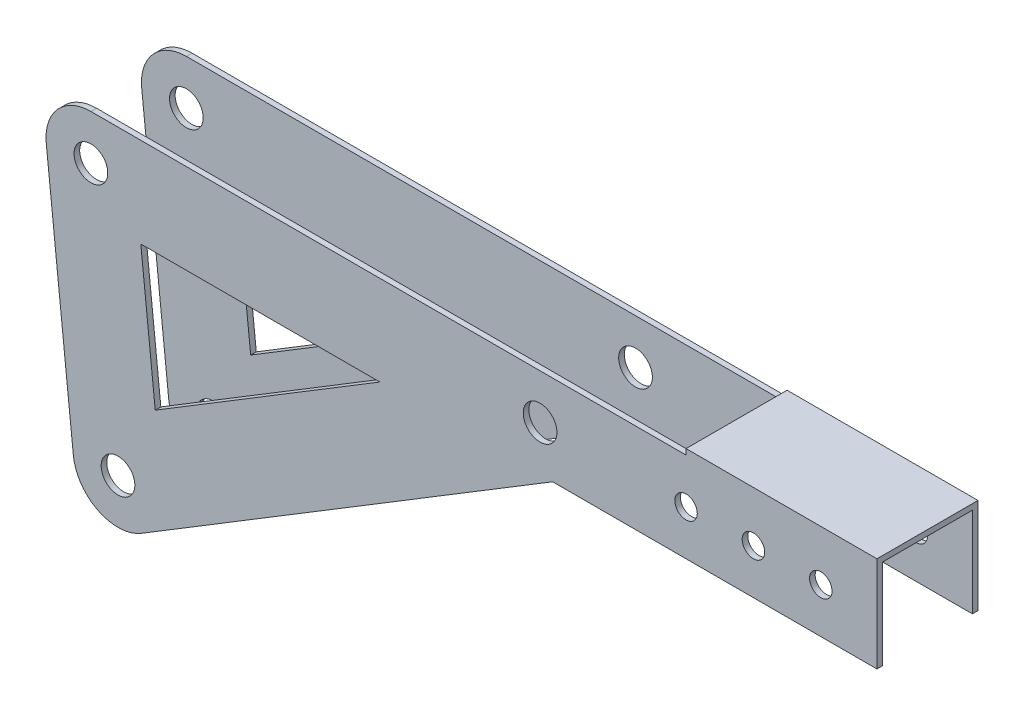
SolidWorks part; units mm, degrees
ref_plane "前视" through (0, 0, 0) normal (0, 0, 1) x (1, 0, 0)
ref_plane "上视" through (0, 0, 0) normal (0, 1, 0) x (1, 0, 0)
ref_plane "右视" through (0, 0, 0) normal (1, 0, 0) x (0, 0, -1)
sketch "草图1" plane through (0, 0, 0) normal (0, 0, 1) x (1, 0, 0)
  line L0 (-22.7233, 3.4621) -> (73.9869, 3.4621) construction
  line L1 (-6.5935, 20.8571) -> (-6.5935, -9.1197) construction
  line L2 (-6.5935, 7.4621) -> (63.4065, 7.4621)
  line L3 (-2.1494, -0.5379) -> (19.1387, -0.5379)
  line L4 (-10.5714, 3.0425) -> (-8.1589, -19.8306)
  line L5 (-2.1016, -22.8281) -> (34.5279, -0.5379)
  line L6 (-0.8655, -12.7111) -> (19.1387, -0.5379)
  line L7 (-2.1494, -0.5379) -> (-0.8655, -12.7111)
  line L8 (63.4065, 7.4621) -> (63.4065, -0.5379)
  line L9 (58.4065, 27.4351) -> (58.4065, -14.6669) construction
  line L10 (52.4065, -14.6579) -> (52.4065, 27.4351) construction
  line L11 (46.4065, 27.4351) -> (46.4065, -14.6579) construction
  line L12 (34.5279, -0.5379) -> (63.4065, -0.5379)
  circle A0 centre (-6.5935, 3.4621) radius 1.5
  circle A1 centre (33.4065, 3.4621) radius 1.5
  circle A2 centre (-4.181, -19.4111) radius 1.5
  arc A3 (-6.5935, 7.4621) -> (-10.5714, 3.0425) centre (-6.5935, 3.4621) ccw
  arc A4 (-8.1589, -19.8306) -> (-2.1016, -22.8281) centre (-4.181, -19.4111) ccw
  circle A5 centre (33.4065, 3.4621) radius 4 construction
  circle A6 centre (58.4065, 3.4621) radius 1
  circle A7 centre (52.4065, 3.4621) radius 1
  circle A8 centre (46.4065, 3.4621) radius 1
  dimension "D1" = 3
  dimension "D2" = 3
  dimension "D3" = 3
  dimension "D7" = 8
  dimension "D8" = 8
  dimension "D9" = 8
  dimension "D14" = 2
  dimension "D15" = 2
  dimension "D16" = 2
  dimension "D4" = 23
  dimension "D5" = 40
  dimension "D6" = 44
  dimension "D10" = 70
  dimension "D11" = 5
  dimension "D12" = 11
  dimension "D13" = 17
extrude "凸台-拉伸1" add sketch "草图1" along normal blind 0.5
ref_plane "基准面1" through (0, 0, -8) normal (0, 0, 1) x (1, 0, 0)
sketch "草图2" plane through (0, 0, -8) normal (0, 0, 1) x (1, 0, 0)
  line L3 (-0.8655, -12.7111) -> (19.1387, -0.5379)
  line L4 (-2.1494, -0.5379) -> (-0.8655, -12.7111)
  line L5 (19.1387, -0.5379) -> (-2.1494, -0.5379)
  line L6 (-0.8655, -12.7111) -> (19.1387, -0.5379)
  line L7 (-2.1494, -0.5379) -> (-0.8655, -12.7111)
  line L8 (19.1387, -0.5379) -> (-2.1494, -0.5379)
  line L11 (-2.1016, -22.8281) -> (34.5279, -0.5379)
  line L12 (-10.5714, 3.0425) -> (-8.1589, -19.8306)
  line L13 (63.4065, 7.4621) -> (-6.5935, 7.4621)
  line L14 (63.4065, -0.5379) -> (63.4065, 7.4621)
  line L15 (34.5279, -0.5379) -> (63.4065, -0.5379)
  line L16 (-2.1016, -22.8281) -> (34.5279, -0.5379)
  line L17 (-10.5714, 3.0425) -> (-8.1589, -19.8306)
  line L18 (63.4065, 7.4621) -> (-6.5935, 7.4621)
  line L19 (63.4065, -0.5379) -> (63.4065, 7.4621)
  line L20 (34.5279, -0.5379) -> (63.4065, -0.5379)
  circle A1 centre (-4.181, -19.4111) radius 1.5
  circle A2 centre (-4.181, -19.4111) radius 1.5
  circle A3 centre (33.4065, 3.4621) radius 1.5
  circle A4 centre (33.4065, 3.4621) radius 1.5
  circle A5 centre (-6.5935, 3.4621) radius 1.5
  circle A6 centre (-6.5935, 3.4621) radius 1.5
  circle A7 centre (52.4065, 3.4621) radius 1
  circle A8 centre (52.4065, 3.4621) radius 1
  circle A9 centre (58.4065, 3.4621) radius 1
  circle A10 centre (58.4065, 3.4621) radius 1
  circle A11 centre (46.4065, 3.4621) radius 1
  circle A12 centre (46.4065, 3.4621) radius 1
  arc A14 (-8.1589, -19.8306) -> (-2.1016, -22.8281) centre (-4.181, -19.4111) ccw
  arc A15 (-6.5935, 7.4621) -> (-10.5714, 3.0425) centre (-6.5935, 3.4621) ccw
  arc A16 (-8.1589, -19.8306) -> (-2.1016, -22.8281) centre (-4.181, -19.4111) ccw
  arc A17 (-6.5935, 7.4621) -> (-10.5714, 3.0425) centre (-6.5935, 3.4621) ccw
  dimension "D1" = 0
  dimension "D2" = 0
  dimension "D3" = 0
  dimension "D4" = 0
  dimension "D5" = 0
  dimension "D6" = 0
  dimension "D7" = 0
  dimension "D8" = 0
extrude "凸台-拉伸2" add sketch "草图2" against normal blind 0.5 separate body
ref_plane "基准面2" through (0, 7.4621, 0) normal (0, 1, 0) x (1, 0, 0)
sketch "草图3" plane through (0, 7.4621, 0) normal (0, 1, 0) x (1, 0, 0)
  line L0 (63.4065, 8.5) -> (63.4065, -0.5)
  line L1 (63.4065, -0.5) -> (46.4065, -0.5)
  line L2 (46.4065, -0.5) -> (46.4065, 0) construction
  line L3 (46.4065, -0.5) -> (46.4065, 8.5)
  line L4 (46.4065, 8.5) -> (46.4065, 8) construction
  line L5 (63.4065, 8.5) -> (-6.5935, 8.5) construction
  line L6 (46.4065, 8.5) -> (63.4065, 8.5)
extrude "凸台-拉伸3" add sketch "草图3" along normal blind 0.5
